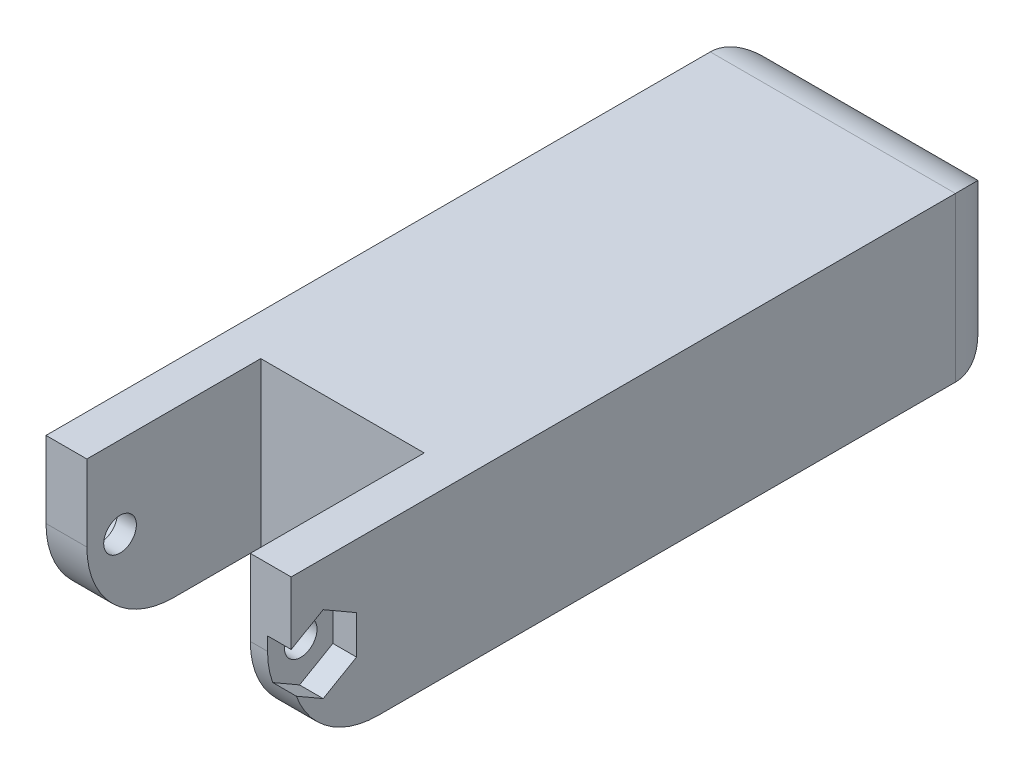
SolidWorks part; units mm, degrees
ref_plane "Front Plane" through (0, 0, 0) normal (0, 0, 1) x (1, 0, 0)
ref_plane "Top Plane" through (0, 0, 0) normal (0, 1, 0) x (1, 0, 0)
ref_plane "Right Plane" through (0, 0, 0) normal (1, 0, 0) x (0, 0, -1)
sketch "Sketch1" plane through (0, 0, 0) normal (0, 1, 0) x (1, 0, 0)
  line L0 (-11.25, 50) -> (18.129, 50) construction
  line L1 (11.25, 16.0513) -> (11.25, -15.092) construction
  line L2 (-11.25, -15.96) -> (25.5084, -15.96) construction
  line L3 (-11.25, 19.1781) -> (-11.25, -18.2188) construction
  line L4 (0, 15.3362) -> (0, -19.7519) construction
  line L5 (-11.25, 50) -> (-11.25, -15.96)
  line L10 (-11.25, -15.96) -> (11.25, -15.96)
  line L11 (11.25, -15.96) -> (11.25, 50)
  line L12 (11.25, 50) -> (-11.25, 50)
  dimension "D1" = 11.25
  dimension "D2" = 11.25
  dimension "D3" = 50
  dimension "D4" = 15.96
extrude "Boss-Extrude1" add sketch "Sketch1" along normal blind 35
ref_plane "Plane1" through (0, 35, 0) normal (0, 1, 0) x (1, 0, 0)
sketch "Sketch2" plane through (0, 35, 0) normal (0, 1, 0) x (1, 0, 0)
  line L0 (-7.5, -15.96) -> (-7.5, 3.1465) construction
  line L1 (-11.25, -15.96) -> (11.25, -15.96) construction
  line L2 (7.5, -15.96) -> (7.5, 3.1465) construction
  line L3 (-11.25, 0) -> (11.25, 0) construction
  line L4 (-11.25, 50) -> (-11.25, -15.96) construction
  line L5 (11.25, -15.96) -> (11.25, 50) construction
  line L6 (-7.5, -15.96) -> (-7.5, 0)
  line L7 (-7.5, 0) -> (7.5, 0)
  line L8 (7.5, 0) -> (7.5, -15.96)
  line L9 (7.5, -15.96) -> (-7.5, -15.96)
  dimension "D1" = 7.5
  dimension "D2" = 7.5
  dimension "D3" = 15.96
extrude "Cut-Extrude1" cut sketch "Sketch2" against normal blind 35
ref_plane "Plane3" through (-11.25, 0, 0) normal (-1, 0, 0) x (0, 0, 1)
sketch "Sketch4" plane through (-11.25, 0, 0) normal (-1, 0, 0) x (0, 0, 1)
  line L0 (10, 35) -> (10, 0) construction
  line L1 (12.375, 35) -> (-12.375, 35) construction
  line L2 (-50, 0) -> (15.96, 0) construction
  line L3 (15.96, 35) -> (15.96, 0) construction
  line L4 (15.96, 17.5) -> (-1.0559, 17.5) construction
  line L5 (12.9155, 35) -> (12.9155, 0) construction
  circle A0 centre (12.9155, 17.5) radius 1.5
  dimension "D3" = 3
  dimension "D1" = 5.96
  dimension "D2" = 17.5
extrude "Cut-Extrude2" cut sketch "Sketch4" against normal blind 35
ref_plane "Plane4" through (-11.25, 0, 0) normal (-1, 0, 0) x (0, 0, 1)
sketch "Sketch5" plane through (-11.25, 0, 0) normal (-1, 0, 0) x (0, 0, 1)
  circle A0 centre (12.9155, 17.5) radius 2.65
  dimension "D1" = 5.3
extrude "Cut-Extrude3" cut sketch "Sketch5" against normal blind 2
ref_plane "Plane5" through (11.25, 0, 0) normal (1, 0, 0) x (0, 0, -1)
sketch "Sketch6" plane through (11.25, 0, 0) normal (1, 0, 0) x (0, 0, -1)
  line L8 (-13.0218, 13.8636) -> (-9.9618, 15.6303)
  line L9 (-9.9618, 15.6303) -> (-9.9618, 19.1637)
  line L10 (-9.9618, 19.1637) -> (-13.0218, 20.9304)
  line L11 (-13.0218, 20.9304) -> (-16.0818, 19.1637)
  line L12 (-16.0818, 19.1637) -> (-16.0818, 15.6303)
  line L13 (-16.0818, 15.6303) -> (-13.0218, 13.8636)
  circle A0 centre (-13.0218, 17.397) radius 3.06 construction
  dimension "D1" = 6.12
extrude "Cut-Extrude4" cut sketch "Sketch6" against normal blind 2.17
sketch "Sketch7" plane through (11.25, 0, 0) normal (1, 0, 0) x (0, 0, -1)
  line L0 (-22.4372, 25) -> (30.4341, 25) construction
  line L1 (-15.96, 0) -> (50, 0) construction
  line L2 (-15.96, 10) -> (-15.96, 0)
  line L3 (-21.897, 10) -> (26.6521, 10) construction
  line L4 (-15.96, 15.56) -> (-15.96, 0) construction
  line L5 (-15.96, 10) -> (54.1371, 10)
  line L6 (54.1371, 10) -> (54.1371, 25)
  line L7 (12.375, 35) -> (-12.375, 35) construction
  line L8 (54.1371, 25) -> (-15.96, 25)
  line L9 (-15.96, 35) -> (-15.96, 19.234) construction
  line L10 (-15.96, 25) -> (-15.96, 35)
  line L11 (-15.96, 35) -> (70.7116, 35)
  line L12 (70.7116, 35) -> (71.1923, 0)
  line L13 (71.1923, 0) -> (-15.96, 0)
  dimension "D1" = 10
  dimension "D2" = 10
extrude "Cut-Extrude5" cut sketch "Sketch7" against normal blind 27.17
fillet "Fillet1" radius 8 2 edges at (9.375, 10, 15.96) (-9.375, 10, 15.96)
fillet "Fillet2" radius 5 4 edges at (11.25, 17.5, -50) (-11.25, 17.5, -50) (0, 10, -50) (0, 25, -50)
sketch "Sketch8" plane through (11.25, 0, 0) normal (1, 0, 0) x (0, 0, -1)
  line L0 (-15.96, 25) -> (45, 25) construction
  line L1 (50, 25) -> (40, 25) construction
  line L2 (45, 25) -> (45, 10) construction
  spline S0 degree 2 poles (48.1885, 18.5557) (41.4664, 20.7103) (45, 25) knots 0 0 0 1 1 1
  point P0 (53.5443, 14.3208)
  point P1 (48.1885, 18.5557)
  point P2 (31.2492, 25)
  point P3 (45, 25)
  point P6 (43.7855, 22.42)
